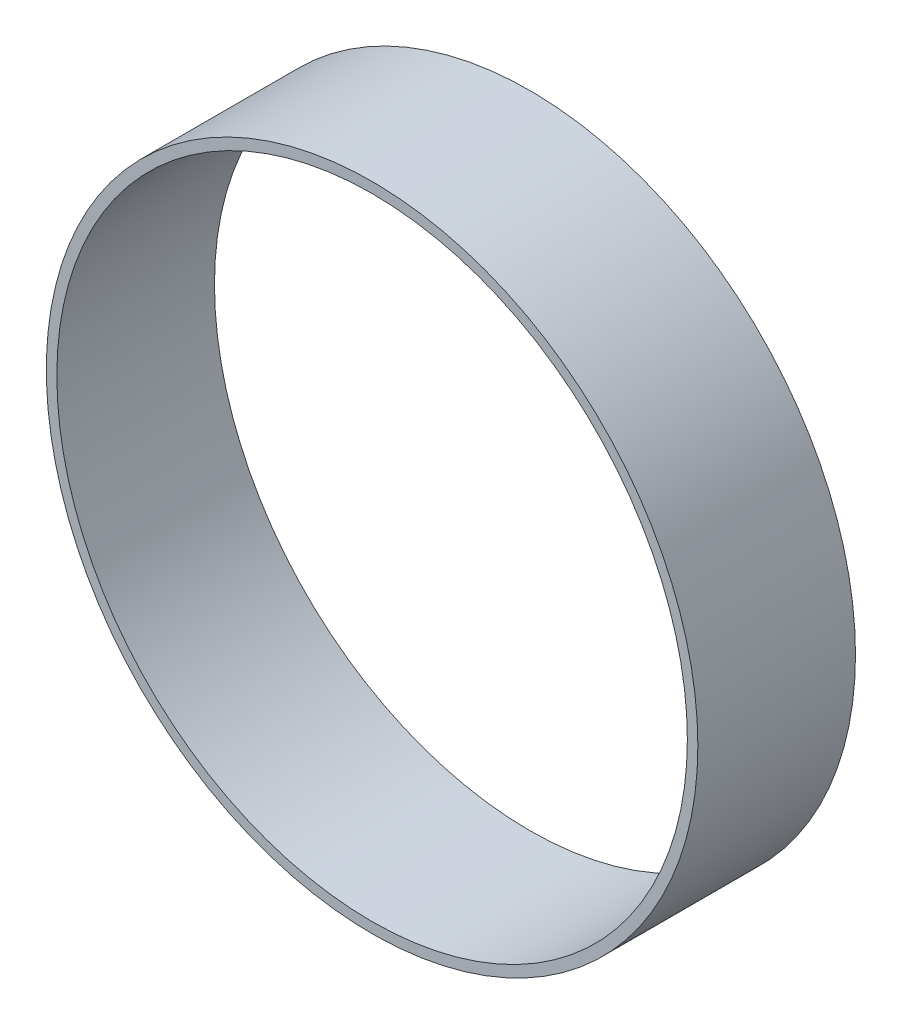
SolidWorks part; units mm, degrees
ref_plane "Plano frontal" through (0, 0, 0) normal (0, 0, 1) x (1, 0, 0)
ref_plane "Plano superior" through (0, 0, 0) normal (0, 1, 0) x (1, 0, 0)
ref_plane "Plano direito" through (0, 0, 0) normal (1, 0, 0) x (0, 0, -1)
sketch "Esboço1" plane through (0, 0, 0) normal (0, 0, 1) x (1, 0, 0)
  circle A0 centre (0, 0) radius 30
  circle A1 centre (0, 0) radius 31
  dimension "D1" = 60
  dimension "D2" = 62
extrude "Ressalto-extrusão1" add sketch "Esboço1" along normal blind 15
